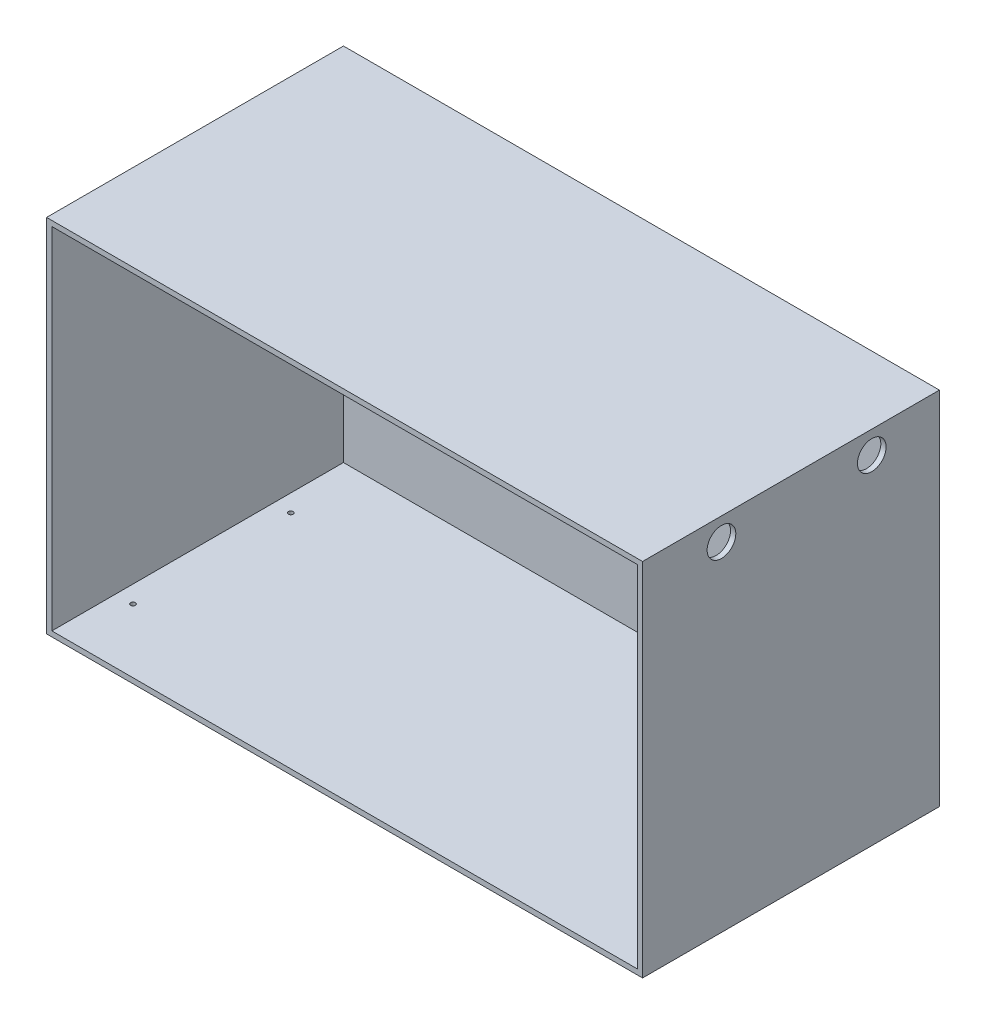
SolidWorks part; units mm, degrees
ref_plane "Alzado" through (0, 0, 0) normal (0, 0, 1) x (1, 0, 0)
ref_plane "Planta" through (0, 0, 0) normal (0, 1, 0) x (1, 0, 0)
ref_plane "Vista lateral" through (0, 0, 0) normal (1, 0, 0) x (0, 0, -1)
sketch "Croquis1" plane through (0, 0, 0) normal (0, 1, 0) x (1, 0, 0)
  line L1 (-396.5, 220) -> (396.5, 220)
  line L2 (-396.5, 220) -> (-396.5, -220)
  line L3 (-396.5, -220) -> (396.5, -220)
  line L4 (396.5, 220) -> (396.5, -220)
  line L5 (-396.5, 220) -> (396.5, -220) construction
  line L6 (-396.5, -220) -> (396.5, 220) construction
  point P0 (0, 0)
  dimension "D1" = 793
  dimension "D2" = 440
extrude "Saliente-Extruir1" add sketch "Croquis1" along normal blind 480
shell "Vaciado1" thickness 7
sketch "Croquis2" plane through (0, 0, 0) normal (0, -1, 0) x (1, 0, 0)
  line L0 (-327.9814, 41.2887) -> (-340.6814, 41.2887) construction
  line L1 (-346.5, 30) -> (-346.5, -220) construction
  line L2 (396.5, -220) -> (-396.5, -220) construction
  line L3 (-396.5, -220) -> (-396.5, 220) construction
  circle A0 centre (-340.6814, 41.2887) radius 12.7
  dimension "D1" = 25.4
  dimension "D2" = 250
  dimension "D3" = 50
extrude "Cortar-Extruir1" cut sketch "Croquis2" against normal blind 80
sketch "Croquis3" plane through (0, 0, 0) normal (0, -1, 0) x (1, 0, 0)
  line L0 (-340.6814, 41.2887) -> (-340.6814, 81.2887) construction
  circle A0 centre (-340.6814, 81.2887) radius 6.35
  dimension "D1" = 12.7
  dimension "D2" = 40
extrude "Cortar-Extruir2" cut sketch "Croquis3" against normal blind 10
sketch "Croquis5" plane through (0, 0, 0) normal (0, -1, 0) x (1, 0, 0)
  line L0 (-340.6814, 81.2887) -> (-340.6814, 121.2887) construction
  circle A0 centre (-340.6814, 121.2887) radius 6.35
  dimension "D2" = 12.7
  dimension "D1" = 40
extrude "Cortar-Extruir4" cut sketch "Croquis5" against normal blind 10
sketch "Croquis6" plane through (-396.5, 0, 0) normal (-1, 0, 0) x (0, 0, 1)
  line L0 (70, 450) -> (220, 450) construction
  line L1 (220, 480) -> (220, 0) construction
  line L2 (70, 450) -> (70, 480) construction
  line L3 (-220, 480) -> (220, 480) construction
  line L4 (70, 450) -> (-219.4947, 450) construction
  circle A0 centre (-130, 450) radius 19.05
  circle A1 centre (70, 450) radius 19.05
  dimension "D4" = 38.1
  dimension "D5" = 38.1
  dimension "D1" = 150
  dimension "D2" = 30
  dimension "D3" = 200
extrude "Cortar-Extruir5" cut sketch "Croquis6" against normal blind 848
sketch "Croquis7" plane through (0, 0, 0) normal (0, -1, 0) x (1, 0, 0)
  line L0 (0, 0) -> (0, 220) construction
  line L1 (-396.5, 220) -> (396.5, 220) construction
mirror "Simetría1" about plane through (0, 0, 0) normal (1, 0, 0) of "Cortar-Extruir1", "Cortar-Extruir2", "Cortar-Extruir4"
sketch "Croquis8" plane through (0, 0, 0) normal (0, -1, 0) x (1, 0, 0)
  line L0 (340.6814, 28.5887) -> (340.6814, -121.4113) construction
  circle A0 centre (340.6814, 41.2887) radius 12.7 construction
  circle A1 centre (340.6814, -121.4113) radius 12.7
  dimension "D1" = 25.4
  dimension "D2" = 150
extrude "Cortar-Extruir6" cut sketch "Croquis8" against normal blind 10
sketch "Croquis9" plane through (0, 7, 0) normal (0, 1, 0) x (1, 0, 0)
  line L1 (-358.2076, 41.3987) -> (-323.1553, 41.3987)
  line L2 (-358.2076, 41.3987) -> (-358.2076, -203.976)
  line L3 (-358.2076, -203.976) -> (-323.1553, -203.976)
  line L4 (-323.1553, 41.3987) -> (-323.1553, -203.976)
  line L5 (-358.2076, 41.3987) -> (-323.1553, -203.976) construction
  line L6 (-358.2076, -203.976) -> (-323.1553, 41.3987) construction
  point P0 (-340.6814, -81.2887)
extrude "Saliente-Extruir2" add sketch "Croquis9" against normal blind 7
sketch "Croquis10" plane through (0, 0, 0) normal (0, -1, 0) x (-1, 0, 0)
  line L0 (275, 175) -> (396.5, 175) construction
  line L1 (396.5, 220) -> (396.5, -220) construction
  line L2 (275, 175) -> (275, 220) construction
  line L3 (-396.5, 220) -> (396.5, 220) construction
  circle A0 centre (-275, 175) radius 3.97
  circle A1 centre (-275, -81.2) radius 3.97
  circle A2 centre (275, 175) radius 3.9688
  circle A3 centre (275, -81.2) radius 3.97
  dimension "D1" = 7.94
  dimension "D2" = 7.94
  dimension "D3" = 7.94
sketch "Croquis12" plane through (0, 0, -213) normal (0, 0, 1) x (1, 0, 0)
  line L0 (0, 7) -> (0, 473) construction
  line L1 (-389.5, 7) -> (389.5, 7) construction
  line L2 (389.5, 473) -> (-389.5, 473) construction
  line L3 (0, 240) -> (24.0252, 240) construction
  line L4 (-389.5, 473) -> (389.5, 473) construction
  line L5 (-369.5, 27) -> (369.5, 27)
  line L6 (-369.5, 27) -> (-369.5, 453)
  line L7 (-369.5, 453) -> (369.5, 453)
  line L8 (369.5, 27) -> (369.5, 453)
  line L9 (-369.5, 27) -> (369.5, 453) construction
  line L10 (-369.5, 453) -> (369.5, 27) construction
  line L11 (389.5, 473) -> (389.5, 7) construction
  dimension "D1" = 20
  dimension "D2" = 20
sketch "Croquis13" plane through (389.5, 0, 0) normal (-1, 0, 0) x (0, 0, 1)
  line L0 (3.5, 7) -> (3.5, 473) construction
  line L1 (220, 7) -> (-213, 7) construction
  line L2 (220, 473) -> (-213, 473) construction
  line L3 (3.5, 473) -> (3.5, 240) construction
  line L4 (3.5, 240) -> (45.2661, 240) construction
  line L5 (220, 473) -> (220, 7) construction
  line L6 (-193, 453) -> (200, 453)
  line L7 (-193, 453) -> (-193, 27)
  line L8 (-193, 27) -> (200, 27)
  line L9 (200, 453) -> (200, 27)
  line L10 (-193, 453) -> (200, 27) construction
  line L11 (-193, 27) -> (200, 453) construction
  dimension "D1" = 20
  dimension "D2" = 20
sketch "Croquis14" plane through (-396.5, 0, 0) normal (-1, 0, 0) x (0, 0, 1)
  line L0 (-183, 480) -> (-183, 393) construction
  line L1 (-193, 27) -> (200, 27)
  line L2 (-193, 27) -> (-193, 453)
  line L3 (-193, 453) -> (200, 453)
  line L4 (200, 27) -> (200, 453)
  line L5 (-193, 27) -> (200, 453) construction
  line L6 (-193, 453) -> (200, 27) construction
  line L7 (-220, 480) -> (220, 480) construction
  line L8 (-183, 393) -> (-220, 393) construction
  line L9 (-220, 480) -> (-220, 0) construction
  line L10 (-193, 453) -> (-193, 403)
  line L11 (-193, 403) -> (200, 403)
  line L12 (3.5, 240) -> (45.2661, 240) construction
  line L13 (3.5, 240) -> (3.5, 173.2105) construction
  line L14 (3.5, 7) -> (3.5, 473) construction
  circle A0 centre (-183, 393) radius 3.175
  circle A1 centre (190, 393) radius 3.175
  circle A2 centre (-183, 37) radius 3.175 construction
  circle A3 centre (190, 37) radius 3.175 construction
  circle A4 centre (-193, 27) radius 3.175
  circle A5 centre (200, 27) radius 3.175
  point P0 (3.5, 240)
  dimension "D4" = 6.35
  dimension "D5" = 10
  dimension "D6" = 10
  dimension "D7" = 6.35
  dimension "D8" = 6.35
  dimension "D9" = 6.35
  dimension "D1" = 10
  dimension "D2" = 10
  dimension "D3" = 50
sketch "Croquis15" plane through (0, 0, 0) normal (0, -1, 0) x (1, 0, 0)
  line L0 (-366.5, -120) -> (-366.5, -220) construction
  line L1 (-366.5, -120) -> (-396.5, -120) construction
  line L2 (-396.5, -220) -> (-396.5, 220) construction
  line L3 (0, 0) -> (0, -220) construction
  line L4 (396.5, -220) -> (-396.5, -220) construction
  line L5 (0, 0) -> (14.2284, 0) construction
  line L6 (0, -15) -> (113.2183, -15) construction
  line L7 (-366.5, 220) -> (-366.5, 90) construction
  line L8 (-396.5, 220) -> (396.5, 220) construction
  circle A0 centre (-366.5, -120) radius 3.175
  circle A1 centre (-366.5, 90) radius 3.175
  circle A2 centre (366.5, -120) radius 3.175
  circle A3 centre (366.5, 90) radius 3.175
  dimension "D3" = 6.35
  dimension "D1" = 30
  dimension "D2" = 100
  dimension "D4" = 130
extrude "Cortar-Extruir10" cut sketch "Croquis15" against normal blind 10
sketch "Croquis16" plane through (-396.5, 0, 0) normal (-1, 0, 0) x (0, 0, 1)
  line L0 (220, 480) -> (220, 0) construction
  line L1 (-225, 401.7269) -> (220, 401.7269)
  line L2 (-225, 401.7269) -> (-225, 0)
  line L3 (-225, 0) -> (220, 0)
  line L4 (220, 401.7269) -> (220, 0)
  line L5 (-225, 401.7269) -> (220, 0) construction
  line L6 (-225, 0) -> (220, 401.7269) construction
  point P0 (-2.5, 200.8635)
sketch "Croquis18" plane through (0, 0, -213) normal (0, 0, 1) x (1, 0, 0)
  line L0 (-348.7422, 441.087) -> (-348, 438) construction
  line L1 (-348, 438) -> (-344.913, 438.7422) construction
  circle A0 centre (-348, 438) radius 3.175
  circle A1 centre (0, 438) radius 3.175
  circle A2 centre (348, 438) radius 3.175
  circle A3 centre (348, 240) radius 3.175
  circle A4 centre (348, 42) radius 3.175
  circle A5 centre (0, 42) radius 3.175
  circle A6 centre (-348, 42) radius 3.175
  circle A7 centre (-348, 240) radius 5.5549
extrude "Cortar-Extruir12" cut sketch "Croquis18" against normal blind 10
sketch "Croquis19" plane through (0, 0, 220) normal (0, 0, 1) x (1, 0, 0)
  line L0 (-389.5, 240) -> (0, 240) construction
  line L1 (-389.5, 473) -> (-389.5, 7) construction
  line L2 (0, 240) -> (0, 0) construction
  line L4 (-396.5, 0) -> (396.5, 0)
  line L5 (-396.5, 0) -> (-396.5, 480)
  line L6 (-396.5, 480) -> (396.5, 480)
  line L7 (396.5, 0) -> (396.5, 480)
  line L8 (-396.5, 0) -> (396.5, 480) construction
  line L9 (-396.5, 480) -> (396.5, 0) construction
extrude "Cortar-Extruir13" cut sketch "Croquis19" against normal blind 45
sketch "Croquis20" plane through (0, 0, 0) normal (0, -1, 0) x (1, 0, 0)
  line L1 (316.4197, 137.6096) -> (356.6426, 137.6096)
  line L2 (316.4197, 137.6096) -> (316.4197, -197.5808)
  line L3 (316.4197, -197.5808) -> (356.6426, -197.5808)
  line L4 (356.6426, 137.6096) -> (356.6426, -197.5808)
  line L5 (316.4197, 137.6096) -> (356.6426, -197.5808) construction
  line L6 (316.4197, -197.5808) -> (356.6426, 137.6096) construction
  point P0 (336.5311, -29.9856)
extrude "Saliente-Extruir3" add sketch "Croquis20" against normal blind 7
sketch "Croquis21" plane through (0, 0, 0) normal (0, -1, 0) x (1, 0, 0)
  line L0 (396.5, -220) -> (316.5, -220) construction
  line L1 (396.5, -220) -> (-396.5, -220) construction
  line L2 (316.5, -220) -> (316.5, 175) construction
  line L3 (-396.5, 175) -> (396.5, 175) construction
  circle A0 centre (316.5, -144.9784) radius 12.7
  dimension "D2" = 25.4
  dimension "D1" = 80
sketch "Croquis22" plane through (0, 0, -220) normal (0, 0, -1) x (-1, 0, 0)
  line L1 (-375.2804, 466.7691) -> (379.4355, 466.7691)
  line L2 (-375.2804, 466.7691) -> (-375.2804, 19.4447)
  line L3 (-375.2804, 19.4447) -> (379.4355, 19.4447)
  line L4 (379.4355, 466.7691) -> (379.4355, 19.4447)
  line L5 (-375.2804, 466.7691) -> (379.4355, 19.4447) construction
  line L6 (-375.2804, 19.4447) -> (379.4355, 466.7691) construction
  point P0 (2.0775, 243.1069)
  point P5 (-375.2804, 466.7691)
extrude "Saliente-Extruir4" add sketch "Croquis22" against normal blind 7
